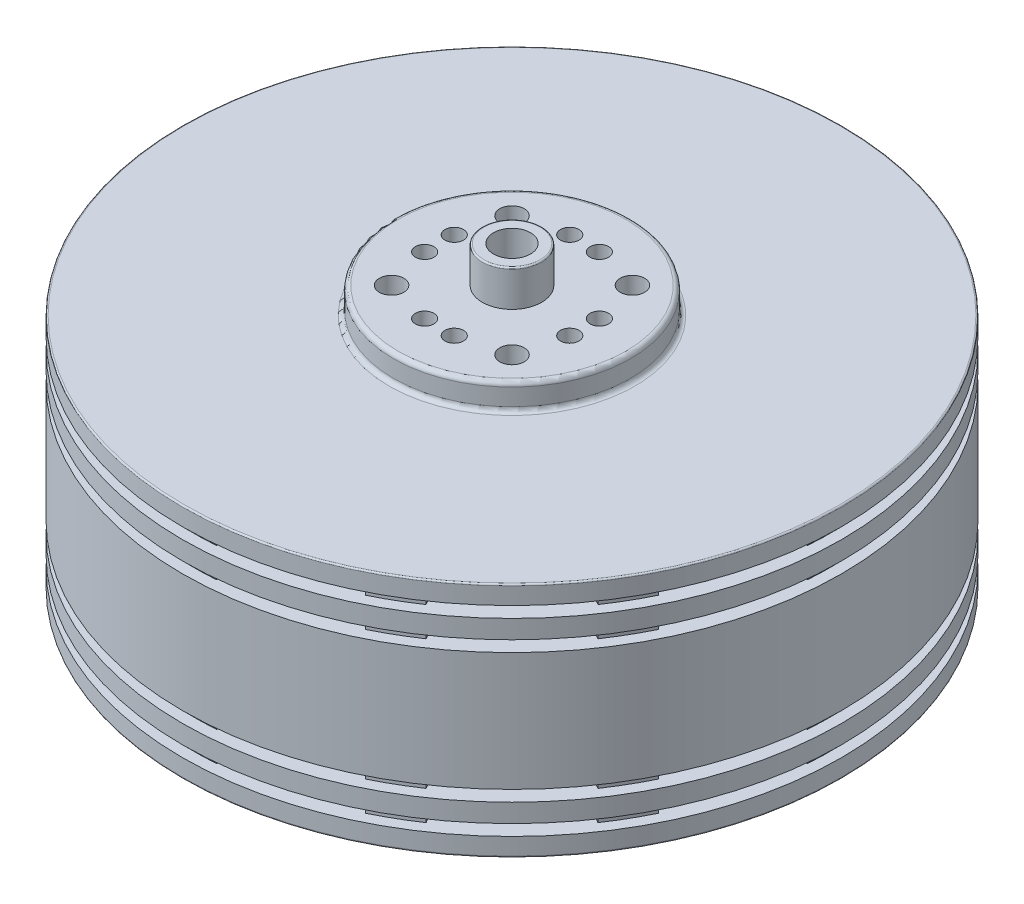
SolidWorks part; units mm, degrees
ref_plane "前视基准面" through (0, 0, 0) normal (0, 0, 1) x (1, 0, 0)
ref_plane "上视基准面" through (0, 0, 0) normal (0, 1, 0) x (1, 0, 0)
ref_plane "右视基准面" through (0, 0, 0) normal (1, 0, 0) x (0, 0, -1)
sketch "草图1" plane through (0, 0, 0) normal (0, 1, 0) x (1, 0, 0)
  circle A0 centre (0, 0) radius 44.5
  dimension "D1" = 89
extrude "凸台-拉伸1" add sketch "草图1" along normal blind 2.5
ref_plane "基准面1" through (0, 4, 0) normal (0, 1, 0) x (1, 0, 0)
sketch "草图2" plane through (0, 4, 0) normal (0, 1, 0) x (1, 0, 0)
  circle A1 centre (0, 0) radius 44.5
  circle A2 centre (0, 0) radius 44.5
  dimension "D1" = 0
extrude "凸台-拉伸2" add sketch "草图2" along normal blind 2.5 separate body
ref_plane "基准面2" through (0, 8, 0) normal (0, 1, 0) x (1, 0, 0)
sketch "草图3" plane through (0, 8, 0) normal (0, 1, 0) x (1, 0, 0)
  circle A1 centre (0, 0) radius 44.5
  circle A2 centre (0, 0) radius 44.5
  dimension "D1" = 0
extrude "凸台-拉伸3" add sketch "草图3" along normal blind 16 separate body
ref_plane "基准面3" through (0, 25.5, 0) normal (0, 1, 0) x (1, 0, 0)
sketch "草图4" plane through (0, 25.5, 0) normal (0, 1, 0) x (1, 0, 0)
  circle A1 centre (0, 0) radius 44.5
  circle A2 centre (0, 0) radius 44.5
  dimension "D1" = 0
extrude "凸台-拉伸4" add sketch "草图4" along normal blind 2.5 separate body
ref_plane "基准面4" through (0, 29.5, 0) normal (0, 1, 0) x (1, 0, 0)
sketch "草图5" plane through (0, 29.5, 0) normal (0, 1, 0) x (1, 0, 0)
  circle A1 centre (0, 0) radius 44.5
  circle A2 centre (0, 0) radius 44.5
  dimension "D1" = 0
extrude "凸台-拉伸5" add sketch "草图5" along normal blind 2.5 separate body
sketch "草图6" plane through (0, 32, 0) normal (0, 1, 0) x (1, 0, 0)
  circle A0 centre (0, 0) radius 16
  dimension "D1" = 32
extrude "凸台-拉伸6" add sketch "草图6" along normal offset from surface (3.5 mm away) 35.5 up to face at (0, 0, 44.5)
sketch "草图7" plane through (0, 35.5, 0) normal (0, 1, 0) x (1, 0, 0)
  circle A0 centre (0, 0) radius 4
  dimension "D1" = 8
extrude "凸台-拉伸7" add sketch "草图7" along normal blind 4.9
sketch "草图8" plane through (0, 32, 0) normal (0, 1, 0) x (1, 0, 0)
  line L0 (0, 39.5) -> (0, 43) construction
  line L1 (3, 39.3859) -> (3, 42.8952)
  line L2 (-3, 39.3859) -> (-3, 42.8952)
  line L3 (-3, 0) -> (-3, 43) construction
  line L4 (3, 0) -> (3, 43) construction
  line L5 (0, 0) -> (0, 43) construction
  arc A0 (3, 42.8952) -> (-3, 42.8952) centre (0, 0) ccw
  arc A1 (3, 39.3859) -> (-3, 39.3859) centre (0, 0) ccw
  dimension "D1" = 86
  dimension "D2" = 79
  dimension "D3" = 3
  dimension "D4" = 3
extrude "凸台-拉伸8" add sketch "草图8" against normal up to surface (29.5 mm away) up to face at (0, 2.5, 44.5)
pattern_circular "阵列(圆周)1" count 12 over 360 about axis through (0, 0, 0) along (0, 1, 0) of "凸台-拉伸8"
fillet "圆角1" radius 0.6 2 edges at (0, 32, 16) (0, 35.5, 16)
fillet "圆角2" radius 0.2 1 edges at (0, 40.4, 4)
fillet "圆角3" radius 0.2 2 edges at (0, 0, 44.5) (0, 32, 44.5)
sketch "草图9" plane through (0, 35.5, 0) normal (0, 1, 0) x (1, 0, 0)
  line L0 (0, 0) -> (0, -6.5041) construction
  line L1 (-8.1317, -8.1317) -> (8.1317, -8.1317) construction
  line L2 (-8.1317, -8.1317) -> (-8.1317, 8.1317) construction
  line L3 (-8.1317, 8.1317) -> (8.1317, 8.1317) construction
  line L4 (8.1317, -8.1317) -> (8.1317, 8.1317) construction
  line L5 (-8.1317, -8.1317) -> (8.1317, 8.1317) construction
  line L6 (-8.1317, 8.1317) -> (8.1317, -8.1317) construction
  circle A0 centre (-8.1317, 8.1317) radius 0.75
  circle A1 centre (8.1317, 8.1317) radius 0.75
  circle A2 centre (8.1317, -8.1317) radius 0.75
  circle A3 centre (-8.1317, -8.1317) radius 0.75
  point P0 (0, 0)
  dimension "D3" = 1.5
  dimension "D2" = 23
  dimension "D4" = 45
extrude "切除-拉伸1" cut sketch "草图9" against normal blind 5
fillet "圆角4" radius 0.1 4 edges at (8.1317, 35.5, -7.3817) (8.1317, 35.5, 8.8817) (-8.1317, 35.5, 8.8817) (-8.1317, 35.5, -7.3817)
sketch "草图10" plane through (0, 0, 0) normal (0, -1, 0) x (1, 0, 0)
  line L1 (-8, -8) -> (8, -8) construction
  line L2 (-8, -8) -> (-8, 8) construction
  line L3 (-8, 8) -> (8, 8) construction
  line L4 (8, -8) -> (8, 8) construction
  line L5 (-8, -8) -> (8, 8) construction
  line L6 (-8, 8) -> (8, -8) construction
  circle A0 centre (-8, 8) radius 1.25
  point P0 (0, 0)
  dimension "D3" = 2.5
  dimension "D1" = 16
  dimension "D2" = 16
extrude "切除-拉伸2" [suppressed] cut sketch "草图10" against normal blind 2
pattern_circular "阵列(圆周)2" [suppressed] count 4 over 360
sketch "草图11" plane through (0, 0, 0) normal (0, -1, 0) x (1, 0, 0)
  circle A0 centre (0, 0) radius 25
  dimension "D1" = 50
extrude "凸台-拉伸9" add sketch "草图11" along normal blind 4
fillet "圆角5" radius 0.5 2 edges at (0, 0, 25) (0, -4, -25)
sketch "草图12" plane through (0, -4, 0) normal (0, -1, 0) x (1, 0, 0)
  line L0 (0, 0) -> (0, 20) construction
  line L1 (0, 0) -> (14.1421, 14.1421) construction
  circle A0 centre (0, 0) radius 20 construction
  circle A1 centre (14.1421, 14.1421) radius 1
  dimension "D1" = 40
  dimension "D3" = 2
  dimension "D2" = 45
extrude "切除-拉伸3" cut sketch "草图12" against normal blind 2
hole_wizard "M4 螺纹孔1" positions "3D草图1" profile "草图13" tap size "M4" standard "GB"
sketch3d "3D草图1"
  line L0 (14.1421, -2, 14.1421) -> (14.1421, -4, 14.1421) construction
  point P0 (14.1421, -4, 14.1421)
sketch "草图13" plane through (14.1421, -4, 14.1421) normal (1, 0, 0) x (0, 0, -1)
  line L0 (0, 0) -> (0, 10.9914)
  line L1 (0, 10.9914) -> (1.65, 10)
  line L2 (1.65, 10) -> (1.65, 0)
  line L5 (1.65, 0) -> (0, 0)
  line L10 (0, 10.9914) -> (-1.65, 10) construction
  line L11 (0, -6.35) -> (0, 107.95) construction
  dimension "螺纹孔钻头直径" = 3.3
  dimension "螺纹孔钻头深度" = 10
  dimension "导头角度" = 118
cosmetic thread "孔螺蚊线1" parameters "D1"=8, "D2"=4
pattern_circular "阵列(圆周)3" count 4 over 360 about axis through (0, 0, 0) along (0, 1, 0) of "M4 螺纹孔1"
sketch "草图14" plane through (0, -4, 0) normal (0, -1, 0) x (1, 0, 0)
  line L0 (0, 0) -> (0, 28.9985) construction
  line L1 (0, 0) -> (14.1421, 14.1421) construction
  line L2 (14.1421, 14.1421) -> (16.7938, 16.7938) construction
  line L3 (2.8284, -2.8284) -> (16.9706, 11.3137) construction
  line L4 (16.9706, 11.3137) -> (19.6222, 13.9654)
  line L5 (-2.8284, 2.8284) -> (11.3137, 16.9706)
  line L6 (11.3137, 16.9706) -> (13.9654, 19.6222)
  line L7 (2.8284, 2.8284) -> (-11.3137, 16.9706)
  line L8 (-11.3137, 16.9706) -> (-13.9654, 19.6222)
  circle A0 centre (0, 0) radius 10
  circle A1 centre (0, 0) radius 11.5
  circle A2 centre (0, 0) radius 20 construction
  circle A3 centre (0, 0) radius 23.75
  arc A4 (10.9839, 16.6408) -> (10.144, 21.4747) centre (8.8626, 18.7621) ccw
  arc A5 (3.6704, 10.8986) -> (5.7229, 11.3797) centre (4.3087, 12.794) ccw
  arc A6 (-3.6704, 10.8986) -> (-5.7229, 11.3797) centre (-4.3087, 12.794) cw
  arc A7 (-10.9839, 16.6408) -> (-10.144, 21.4747) centre (-8.8626, 18.7621) cw
  dimension "D1" = 47.5
  dimension "D2" = 20
  dimension "D3" = 23
  dimension "D4" = 40
  dimension "D8" = 4
  dimension "D9" = 6
  dimension "D7" = 45
  dimension "D5" = 4
  dimension "D6" = 4
extrude "切除-拉伸4" cut sketch "草图14" against normal blind 2 contours A7 L7 A6 A1 A5 L5 A4 A3
pattern_circular "阵列(圆周)4" count 4 over 360 about axis through (0, 0, 0) along (0, 1, 0) of "切除-拉伸4"
sketch "草图15" plane through (0, -4, 0) normal (0, -1, 0) x (1, 0, 0)
  circle A0 centre (0, 0) radius 10
  dimension "D1" = 20
extrude "切除-拉伸5" cut sketch "草图15" against normal blind 2
sketch "草图16" plane through (0, 35.5, 0) normal (0, 1, 0) x (1, 0, 0)
  line L0 (0, 0) -> (0, 13.6977) construction
  circle A0 centre (0, 0) radius 10 construction
  circle A2 centre (2, 9.798) radius 1
  circle A3 centre (-2, 9.798) radius 1
  dimension "D1" = 20
  dimension "D2" = 2
  dimension "D3" = 2
extrude "切除-拉伸6" cut sketch "草图16" against normal blind 2
hole_wizard "M4 螺纹孔2" positions "3D草图2" profile "草图17" tap size "M4" standard "GB"
sketch3d "3D草图2"
  line L0 (8.1317, 34.9188, -8.1317) -> (8.1317, 36.3625, -8.1317) construction
  point P0 (8.1317, 35.5, -8.1317)
sketch "草图17" plane through (8.1317, 35.5, -8.1317) normal (1, 0, 0) x (0, 0, 1)
  line L0 (0, 0) -> (0, 11.0914)
  line L1 (0, 11.0914) -> (1.65, 10.1)
  line L2 (1.65, 10.1) -> (1.65, 0)
  line L5 (1.65, 0) -> (0, 0)
  line L10 (0, 11.0914) -> (-1.65, 10.1) construction
  line L11 (0, -6.35) -> (0, 107.95) construction
  dimension "螺纹孔钻头直径" = 3.3
  dimension "螺纹孔钻头深度" = 10.1
  dimension "导头角度" = 118
cosmetic thread "孔螺蚊线2" parameters "D1"=8, "D2"=4
pattern_circular "阵列(圆周)5" count 4 over 360 about axis through (0, 0, 0) along (0, 1, 0) of "M4 螺纹孔2"
hole_wizard "M3 螺纹孔1" positions "3D草图3" profile "草图18" tap size "M3" standard "GB"
sketch3d "3D草图3"
  line L0 (2, 33.5, -9.798) -> (2, 35.5, -9.798) construction
  line L1 (-2, 33.5, -9.798) -> (-2, 35.5, -9.798) construction
  point P0 (2, 35.5, -9.798)
  point P4 (-2, 35.5, -9.798)
sketch "草图18" plane through (2, 35.5, -9.798) normal (1, 0, 0) x (0, 0, 1)
  line L0 (0, 0) -> (0, 8.2511)
  line L1 (0, 8.2511) -> (1.25, 7.5)
  line L2 (1.25, 7.5) -> (1.25, 0)
  line L5 (1.25, 0) -> (0, 0)
  line L10 (0, 8.2511) -> (-1.25, 7.5) construction
  line L11 (0, -6.35) -> (0, 107.95) construction
  dimension "螺纹孔钻头直径" = 2.5
  dimension "螺纹孔钻头深度" = 7.5
  dimension "导头角度" = 118
cosmetic thread "孔螺蚊线3" parameters "D1"=6, "D2"=3
cosmetic thread "孔螺蚊线4" parameters "D1"=6, "D2"=3
pattern_circular "阵列(圆周)6" count 4 over 360 about axis through (0, 0, 0) along (0, 1, 0) of "M3 螺纹孔1"
hole_wizard "M6 螺纹孔1" positions "3D草图4" profile "草图19" tap size "M6" standard "GB"
sketch3d "3D草图4"
  line L0 (0, 37.9369, 0) -> (0, 44.7262, 0) construction
  point P0 (0, 40.4, 0)
sketch "草图19" plane through (0, 40.4, 0) normal (1, 0, 0) x (0, 0, 1)
  line L0 (0, 0) -> (0, 16.5022)
  line L1 (0, 16.5022) -> (2.5, 15)
  line L2 (2.5, 15) -> (2.5, 0)
  line L5 (2.5, 0) -> (0, 0)
  line L10 (0, 16.5022) -> (-2.5, 15) construction
  line L11 (0, -6.35) -> (0, 107.95) construction
  dimension "螺纹孔钻头直径" = 5
  dimension "螺纹孔钻头深度" = 15
  dimension "导头角度" = 118
cosmetic thread "孔螺蚊线5" parameters "D1"=12, "D2"=6
